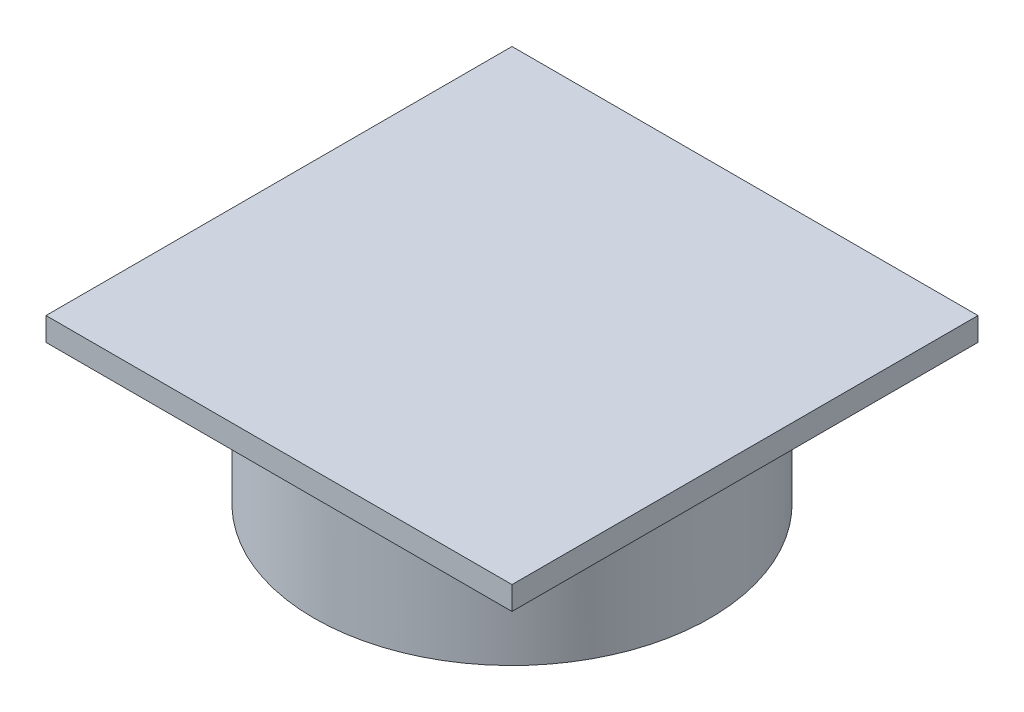
SolidWorks part; units mm, degrees
ref_plane "Alzado" through (0, 0, 0) normal (0, 0, 1) x (1, 0, 0)
ref_plane "Planta" through (0, 0, 0) normal (0, 1, 0) x (1, 0, 0)
ref_plane "Vista lateral" through (0, 0, 0) normal (1, 0, 0) x (0, 0, -1)
sketch "Croquis1" plane through (0, 0, 0) normal (0, 1, 0) x (1, 0, 0)
  circle A0 centre (0, 0) radius 42.5
  dimension "D1" = 85
extrude "Saliente-Extruir1" add sketch "Croquis1" along normal blind 30
sketch "Croquis2" plane through (0, 30, 0) normal (0, 1, 0) x (1, 0, 0)
  line L1 (50, 50) -> (-50, 50)
  line L2 (50, 50) -> (50, -50)
  line L3 (50, -50) -> (-50, -50)
  line L4 (-50, 50) -> (-50, -50)
  line L5 (50, 50) -> (-50, -50) construction
  line L6 (50, -50) -> (-50, 50) construction
  point P0 (0, 0)
  dimension "D1" = 100
extrude "Saliente-Extruir2" add sketch "Croquis2" along normal blind 5
fillet "Redondeo1" radius 5 1 edges at (0, 30, 42.5)
sketch "Croquis3" plane through (0, 0, 0) normal (0, -1, 0) x (1, 0, 0)
  line L0 (0, 0) -> (-26.8701, 26.8701) construction
  line L1 (0, 0) -> (13.435, 13.435) construction
  circle A0 centre (-26.8701, 26.8701) radius 2
  circle A1 centre (26.8701, -26.8701) radius 2
  dimension "D1" = 4
  dimension "D2" = 38
extrude "Cortar-Extruir1" cut sketch "Croquis3" against normal blind 20
